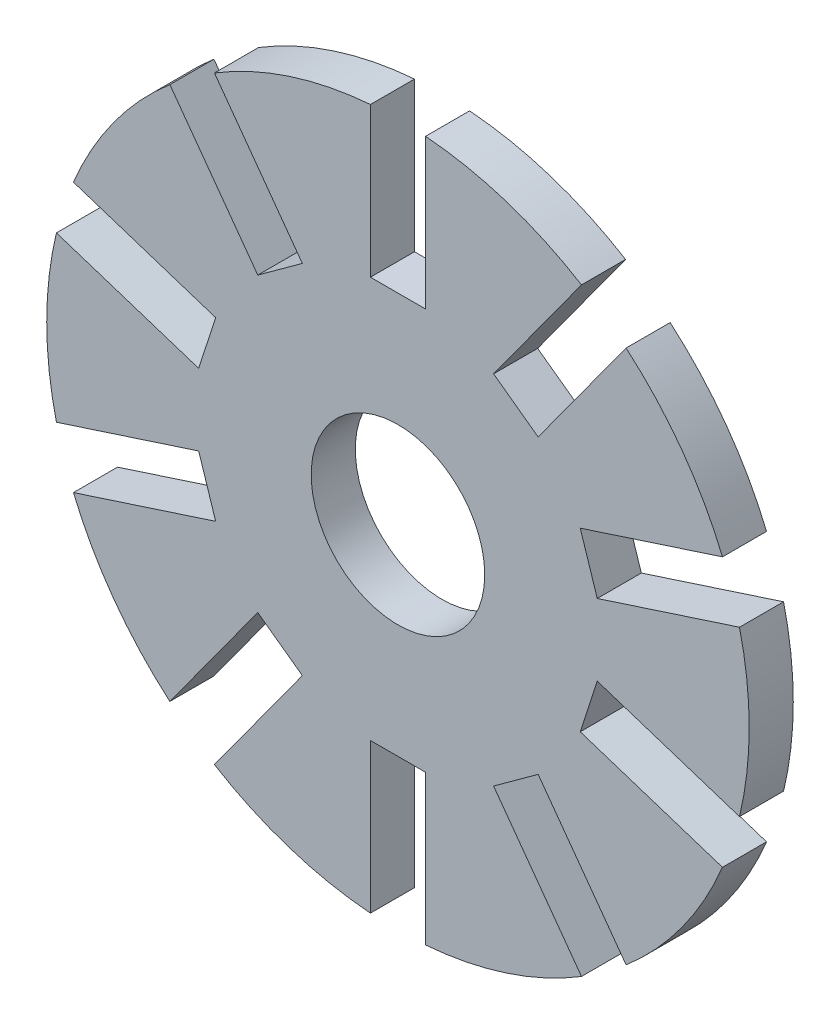
SolidWorks part; units mm, degrees
material "1060-H16"
ref_plane "Спереди" through (0, 0, 0) normal (0, 0, 1) x (1, 0, 0)
ref_plane "Сверху" through (0, 0, 0) normal (0, 1, 0) x (1, 0, 0)
ref_plane "Справа" through (0, 0, 0) normal (1, 0, 0) x (0, 0, -1)
sketch "Эскиз1" plane through (0, 0, 0) normal (0, 0, 1) x (1, 0, 0)
  circle A0 centre (0, 0) radius 12.75
  circle A1 centre (0, 0) radius 3.15
  dimension "D1" = 6.3
  dimension "D2" = 25.5
extrude "Бобышка-Вытянуть1" add sketch "Эскиз1" along normal blind 1.6
sketch "Эскиз3" plane through (0, 0, 0) normal (0, 0, -1) x (-1, 0, 0)
  line L0 (0, 0) -> (0, -12.75) construction
  line L1 (0, -12.75) -> (0, -7.2821)
  line L2 (-7.4943, -10.315) -> (-4.2803, -5.8913)
  line L3 (-12.126, -3.94) -> (-6.9257, -2.2503)
  line L4 (-12.126, 3.94) -> (-6.9257, 2.2503)
  line L5 (-7.4943, 10.315) -> (-4.2803, 5.8913)
  line L6 (0, 12.75) -> (0, 7.2821)
  line L7 (7.4943, 10.315) -> (4.2803, 5.8913)
  line L8 (12.126, 3.94) -> (6.9257, 2.2503)
  line L9 (12.126, -3.94) -> (6.9257, -2.2503)
  line L10 (7.4943, -10.315) -> (4.2803, -5.8913)
  circle A0 centre (0, 0) radius 12.75 construction
  point P27 (0, 0)
  dimension "D1" = 10
extrude "Вырез-Вытянуть-Тонкостенный3" cut sketch "Эскиз3" against normal through all thin thin type two direction wall 1 second wall 1
